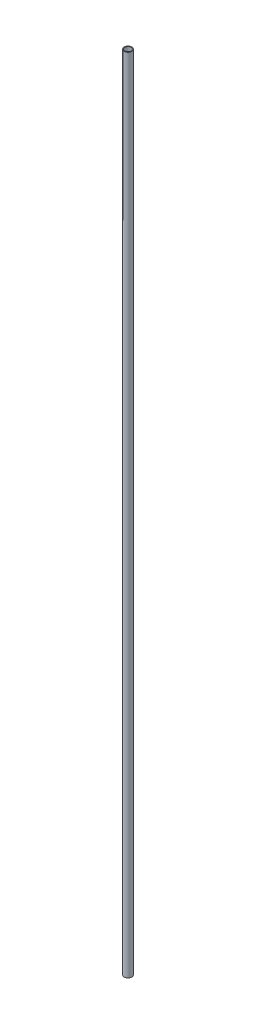
SolidWorks part; units mm, degrees
material "6061-T6 (SS)"
ref_plane "Front Plane" through (0, 0, 0) normal (0, 0, 1) x (1, 0, 0)
ref_plane "Top Plane" through (0, 0, 0) normal (0, 1, 0) x (1, 0, 0)
ref_plane "Right Plane" through (0, 0, 0) normal (1, 0, 0) x (0, 0, -1)
sketch "Sketch1" plane through (0, 0, 0) normal (0, 1, 0) x (1, 0, 0)
  circle A0 centre (0, 0) radius 6.35
  circle A1 centre (0, 0) radius 5.1054
  dimension "D1" = 12.7
  dimension "D2" = 10.2108
extrude "Boss-Extrude1" add sketch "Sketch1" along normal blind 1320.8
ref_point "Point2"
